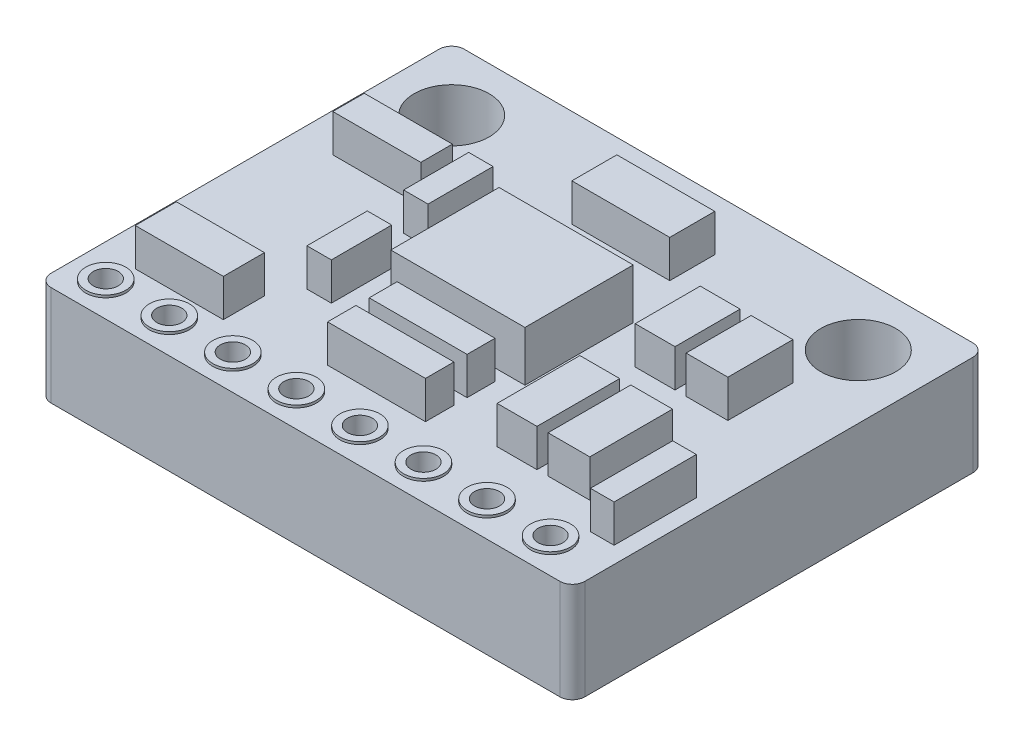
SolidWorks part; units mm, degrees
ref_plane "Plano frontal" through (0, 0, 0) normal (0, 0, 1) x (1, 0, 0)
ref_plane "Plano superior" through (0, 0, 0) normal (0, 1, 0) x (1, 0, 0)
ref_plane "Plano direito" through (0, 0, 0) normal (1, 0, 0) x (0, 0, -1)
sketch "Esboço3" plane through (0, 0, 0) normal (0, 1, 0) x (1, 0, 0)
  line L1 (10.668, -8.255) -> (-10.668, -8.255)
  line L2 (10.668, -8.255) -> (10.668, 8.255)
  line L3 (10.668, 8.255) -> (-10.668, 8.255)
  line L4 (-10.668, -8.255) -> (-10.668, 8.255)
  line L5 (10.668, -8.255) -> (-10.668, 8.255) construction
  line L6 (10.668, 8.255) -> (-10.668, -8.255) construction
  point P0 (0, 0)
extrude "Ressalto-extrusão2" add sketch "Esboço3" along normal blind 4 contours L3 L4 L1 L2
ref_plane "Plano1" through (0, 4, 0) normal (0, 1, 0) x (1, 0, 0)
sketch "Esboço4" plane through (0, 4, 0) normal (0, 1, 0) x (1, 0, 0)
  line L0 (-10.668, -8.255) -> (-10.668, 5.715) construction
  line L1 (-10.668, -8.255) -> (-10.668, 8.255) construction
  line L3 (-10.668, 5.715) -> (-8.128, 5.715) construction
  line L4 (-8.128, 5.715) -> (8.128, 5.715) construction
  circle A0 centre (-8.128, 5.715) radius 1.5
  circle A1 centre (8.128, 5.715) radius 1.5
sketch "Esboço5" plane through (0, 4, 0) normal (0, 1, 0) x (1, 0, 0)
  line L0 (-10.668, 5.715) -> (-8.128, 5.715) construction
extrude "Corte-extrusão1" cut sketch "Esboço4" against normal blind 4
fillet "Filete1" radius 0.5 1 edges at (-10.668, 2, -8.255)
fillet "Filete2" radius 0.5 1 edges at (10.668, 2, -8.255)
fillet "Filete3" radius 0.5 1 edges at (-10.668, 2, 8.255)
fillet "Filete4" radius 0.5 1 edges at (10.668, 2, 8.255)
sketch "Esboço6" plane through (0, 4, 0) normal (0, 1, 0) x (1, 0, 0)
  line L1 (2.6817, -2.1645) -> (-2.6817, -2.1645)
  line L2 (2.6817, -2.1645) -> (2.6817, 2.1645)
  line L3 (2.6817, 2.1645) -> (-2.6817, 2.1645)
  line L4 (-2.6817, -2.1645) -> (-2.6817, 2.1645)
  line L5 (2.6817, -2.1645) -> (-2.6817, 2.1645) construction
  line L6 (2.6817, 2.1645) -> (-2.6817, -2.1645) construction
  point P0 (0, 0)
extrude "Ressalto-extrusão3" add sketch "Esboço6" along normal blind 2 contours L2 L1 L4 L3
sketch "Esboço7" plane through (0, 4, 0) normal (0, 1, 0) x (1, 0, 0)
  line L1 (-9.1362, -4.2798) -> (-5.6154, -4.2798)
  line L2 (-9.1362, -4.2798) -> (-9.1362, -5.924)
  line L3 (-9.1362, -5.924) -> (-5.6154, -5.924)
  line L4 (-5.6154, -4.2798) -> (-5.6154, -5.924)
  line L5 (-9.1362, -4.2798) -> (-5.6154, -5.924) construction
  line L6 (-9.1362, -5.924) -> (-5.6154, -4.2798) construction
  line L7 (-9.1362, 3.2325) -> (-5.6154, 3.2325)
  line L8 (-9.1362, 3.2325) -> (-9.1362, 1.9708)
  line L9 (-9.1362, 1.9708) -> (-5.6154, 1.9708)
  line L10 (-5.6154, 3.2325) -> (-5.6154, 1.9708)
  line L11 (-9.1362, 3.2325) -> (-5.6154, 1.9708) construction
  line L12 (-9.1362, 1.9708) -> (-5.6154, 3.2325) construction
  line L13 (-1.9571, 6.1494) -> (1.9571, 6.1494)
  line L14 (-1.9571, 6.1494) -> (-1.9571, 4.3489)
  line L15 (-1.9571, 4.3489) -> (1.9571, 4.3489)
  line L16 (1.9571, 6.1494) -> (1.9571, 4.3489)
  line L17 (-1.9571, 6.1494) -> (1.9571, 4.3489) construction
  line L18 (-1.9571, 4.3489) -> (1.9571, 6.1494) construction
  line L19 (4.254, 3.2715) -> (5.8458, 3.2715)
  line L20 (4.254, 3.2715) -> (4.254, 0.67)
  line L21 (4.254, 0.67) -> (5.8458, 0.67)
  line L22 (5.8458, 3.2715) -> (5.8458, 0.67)
  line L23 (4.254, 3.2715) -> (5.8458, 0.67) construction
  line L24 (4.254, 0.67) -> (5.8458, 3.2715) construction
  line L25 (6.2888, 3.2715) -> (7.9586, 3.2715)
  line L26 (6.2888, 3.2715) -> (6.2888, 0.67)
  line L27 (6.2888, 0.67) -> (7.9586, 0.67)
  line L28 (7.9586, 3.2715) -> (7.9586, 0.67)
  line L29 (6.2888, 3.2715) -> (7.9586, 0.67) construction
  line L30 (6.2888, 0.67) -> (7.9586, 3.2715) construction
  line L31 (4.254, -1.5398) -> (5.8458, -1.5398)
  line L32 (4.254, -1.5398) -> (4.254, -4.8482)
  line L33 (4.254, -4.8482) -> (5.8458, -4.8482)
  line L34 (5.8458, -1.5398) -> (5.8458, -4.8482)
  line L35 (4.254, -1.5398) -> (5.8458, -4.8482) construction
  line L36 (4.254, -4.8482) -> (5.8458, -1.5398) construction
  line L37 (6.2888, -1.5398) -> (7.9586, -1.5398)
  line L38 (6.2888, -1.5398) -> (6.2888, -4.8482)
  line L39 (6.2888, -4.8482) -> (7.9586, -4.8482)
  line L40 (7.9586, -1.5398) -> (7.9586, -4.8482)
  line L41 (6.2888, -1.5398) -> (7.9586, -4.8482) construction
  line L42 (6.2888, -4.8482) -> (7.9586, -1.5398) construction
  line L43 (10.0049, -2.6357) -> (9.0592, -2.6357)
  line L44 (10.0049, -2.6357) -> (10.0049, -5.924)
  line L45 (10.0049, -5.924) -> (9.0592, -5.924)
  line L46 (9.0592, -2.6357) -> (9.0592, -5.924)
  line L47 (10.0049, -2.6357) -> (9.0592, -5.924) construction
  line L48 (10.0049, -5.924) -> (9.0592, -2.6357) construction
  line L49 (-5.0033, 3.2715) -> (-4.0273, 3.2715)
  line L50 (-5.0033, 3.2715) -> (-5.0033, 0.67)
  line L51 (-5.0033, 0.67) -> (-4.0273, 0.67)
  line L52 (-4.0273, 3.2715) -> (-4.0273, 0.67)
  line L53 (-5.0033, 3.2715) -> (-4.0273, 0.67) construction
  line L54 (-5.0033, 0.67) -> (-4.0273, 3.2715) construction
  line L55 (-5.0033, -0.7812) -> (-4.0273, -0.7812)
  line L56 (-5.0033, -0.7812) -> (-5.0033, -3.194)
  line L57 (-5.0033, -3.194) -> (-4.0273, -3.194)
  line L58 (-4.0273, -0.7812) -> (-4.0273, -3.194)
  line L59 (-5.0033, -0.7812) -> (-4.0273, -3.194) construction
  line L60 (-5.0033, -3.194) -> (-4.0273, -0.7812) construction
  line L61 (1.9571, -3.7523) -> (-1.9571, -3.7523)
  line L62 (1.9571, -3.7523) -> (1.9571, -2.6357)
  line L63 (1.9571, -2.6357) -> (-1.9571, -2.6357)
  line L64 (-1.9571, -3.7523) -> (-1.9571, -2.6357)
  line L65 (1.9571, -3.7523) -> (-1.9571, -2.6357) construction
  line L66 (1.9571, -2.6357) -> (-1.9571, -3.7523) construction
  line L67 (1.9571, -5.4165) -> (-1.9571, -5.4165)
  line L68 (1.9571, -5.4165) -> (1.9571, -4.2798)
  line L69 (1.9571, -4.2798) -> (-1.9571, -4.2798)
  line L70 (-1.9571, -5.4165) -> (-1.9571, -4.2798)
  line L71 (1.9571, -5.4165) -> (-1.9571, -4.2798) construction
  line L72 (1.9571, -4.2798) -> (-1.9571, -5.4165) construction
  point P0 (-7.3758, -5.1019)
  point P5 (-7.3758, 2.6016)
  point P10 (0, 5.2492)
  point P15 (5.0499, 1.9708)
  point P20 (7.1237, 1.9708)
  point P25 (5.0499, -3.194)
  point P30 (7.1237, -3.194)
  point P35 (9.5321, -4.2798)
  point P40 (-4.5153, 1.9708)
  point P45 (-4.5153, -1.9876)
  point P50 (0, -3.194)
  point P55 (0, -4.8482)
extrude "Ressalto-extrusão4" add sketch "Esboço7" along normal blind 1.5
sketch "Esboço8" plane through (0, 4, 0) normal (0, 1, 0) x (1, 0, 0)
  line L2 (10.168, -8.255) -> (-10.168, -8.255) construction
  line L3 (-9.2857, -8.255) -> (-9.2857, -6.9538) construction
  line L4 (-9.2857, -6.9538) -> (-10.668, -6.9538) construction
  line L5 (-10.668, -7.755) -> (-10.668, 7.755) construction
  circle A1 centre (-9.2857, -6.9538) radius 0.8
  circle A2 centre (-6.7457, -6.9538) radius 0.8
  circle A3 centre (-4.2057, -6.9538) radius 0.8
  circle A4 centre (-1.6657, -6.9538) radius 0.8
  circle A5 centre (0.8743, -6.9538) radius 0.8
  circle A6 centre (3.4143, -6.9538) radius 0.8
  circle A7 centre (5.9543, -6.9538) radius 0.8
  circle A8 centre (8.4943, -6.9538) radius 0.8
  dimension "D1" = 8
extrude "Ressalto-extrusão5" add sketch "Esboço8" along normal blind 0.1
sketch "Esboço9" plane through (0, 4, 0) normal (0, 1, 0) x (1, 0, 0)
  circle A0 centre (-9.2857, -6.9538) radius 0.5
  circle A1 centre (-6.7457, -6.9538) radius 0.5
  circle A2 centre (-4.2057, -6.9538) radius 0.5
  circle A3 centre (-1.6657, -6.9538) radius 0.5
  circle A4 centre (0.8743, -6.9538) radius 0.5
  circle A5 centre (3.4143, -6.9538) radius 0.5
  circle A6 centre (5.9543, -6.9538) radius 0.5
  circle A7 centre (8.4943, -6.9538) radius 0.5
  dimension "D1" = 8
extrude "Corte-extrusão2" cut sketch "Esboço9" against normal up to next and the other way up to next
